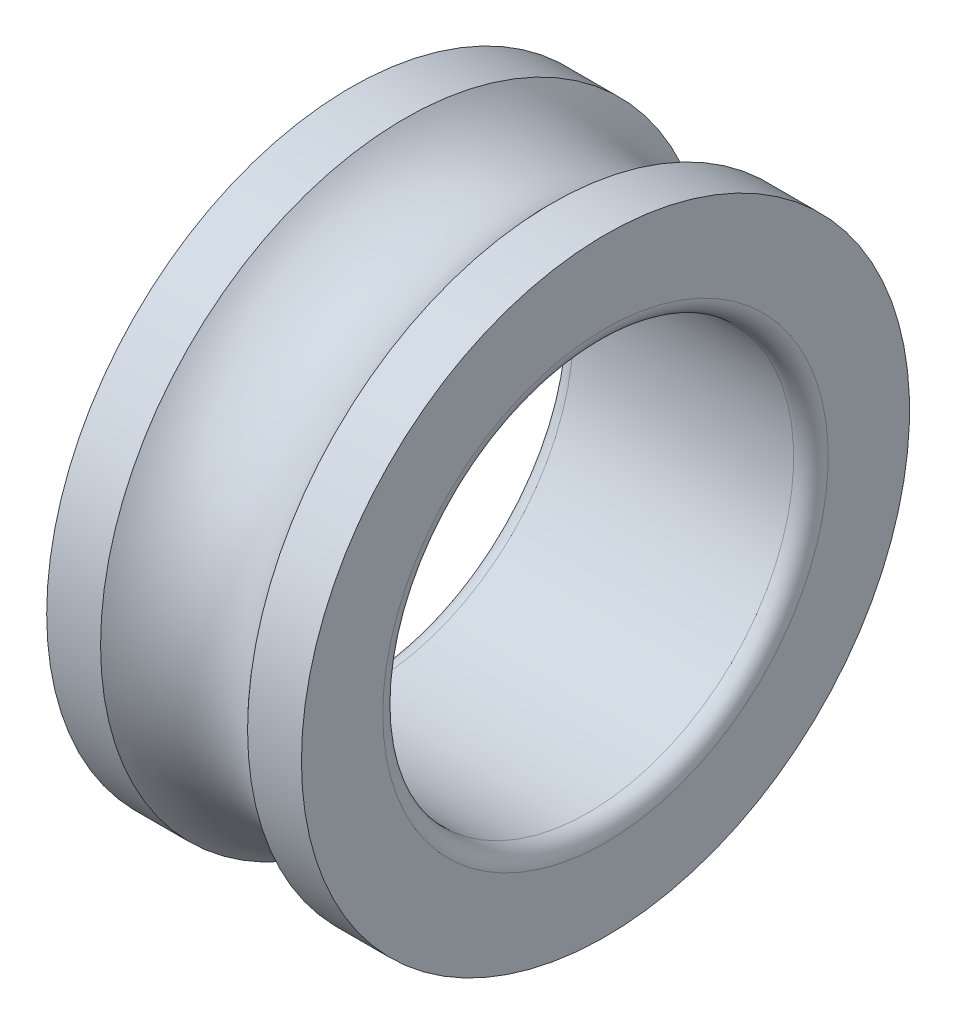
SolidWorks part; units mm, degrees
ref_plane "Front Plane" through (0, 0, 0) normal (0, 0, 1) x (1, 0, 0)
ref_plane "Top Plane" through (0, 0, 0) normal (0, 1, 0) x (1, 0, 0)
ref_plane "Right Plane" through (0, 0, 0) normal (1, 0, 0) x (0, 0, -1)
sketch "Sketch1" plane through (0, 0, 0) normal (0, 0, 1) x (1, 0, 0)
  line L0 (-21.7042, 0) -> (57.4898, 0) construction
  line L1 (0, 0) -> (0, 25) construction
  line L2 (15.5, 37) -> (8.9443, 37)
  line L3 (15.5, 37) -> (15.5, 27.1)
  line L4 (13.4, 25) -> (-13.4, 25)
  line L5 (-15.5, 37) -> (-15.5, 27.1)
  line L6 (15.5, 37) -> (-15.5, 25) construction
  line L7 (15.5, 25) -> (-15.5, 37) construction
  line L8 (-8.9443, 37) -> (-15.5, 37)
  arc A0 (-8.9443, 37) -> (8.9443, 37) centre (0, 45) ccw
  arc A1 (15.5, 27.1) -> (13.4, 25) centre (13.4, 27.1) cw
  arc A2 (-13.4, 25) -> (-15.5, 27.1) centre (-13.4, 27.1) cw
  point P3 (0, 31)
  dimension "D5" = 12
  dimension "D6" = 2.1
  dimension "D1" = 31
  dimension "D2" = 25
  dimension "D3" = 37
  dimension "D4" = 8
revolve "Revolve1" add sketch "Sketch1" angle 360 about L0
